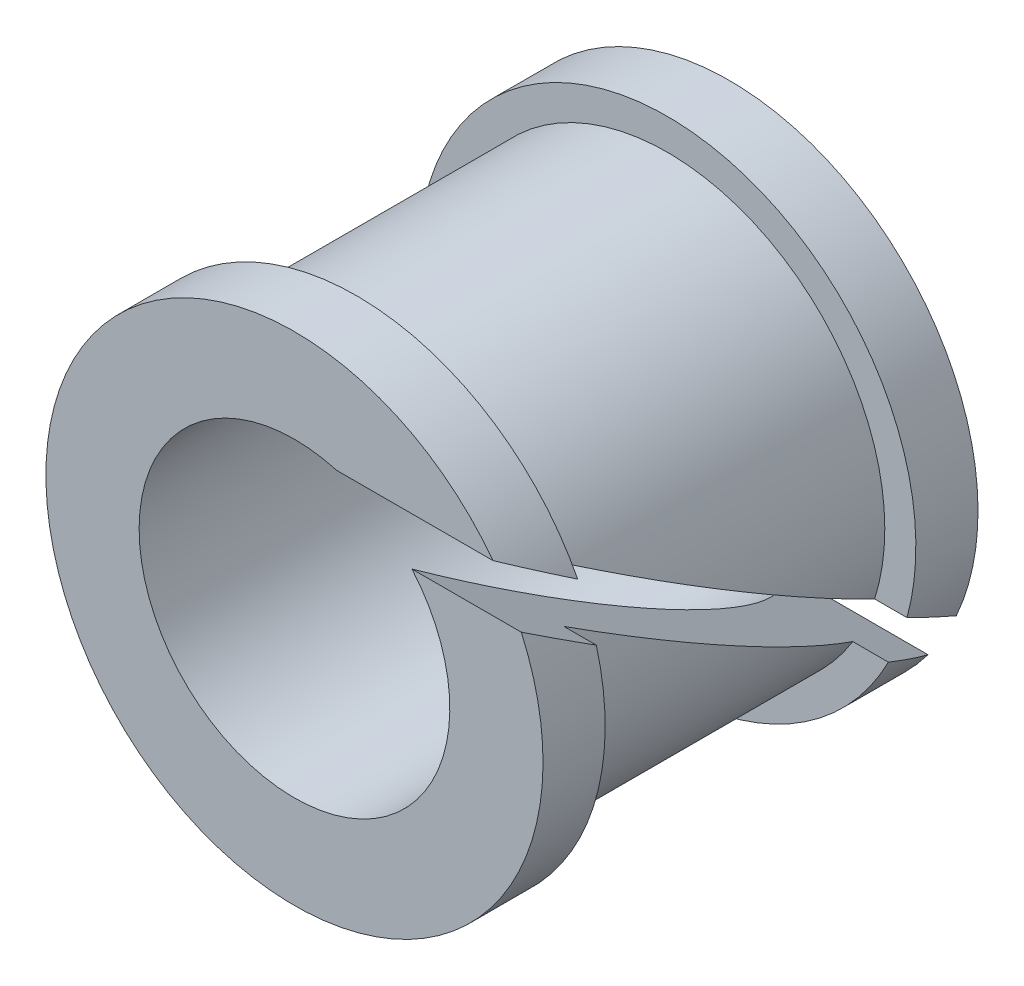
SolidWorks part; units mm, degrees
ref_plane "Front Plane" through (0, 0, 0) normal (0, 0, 1) x (1, 0, 0)
ref_plane "Top Plane" through (0, 0, 0) normal (0, 1, 0) x (1, 0, 0)
ref_plane "Right Plane" through (0, 0, 0) normal (1, 0, 0) x (0, 0, -1)
sketch "Sketch1" plane through (0, 0, 0) normal (1, 0, 0) x (0, 0, -1)
  line L0 (-1.5, 2.4) -> (-1.5, 2.1)
  line L1 (-1.5, 2.1) -> (1.5, 2.1)
  line L2 (1.5, 2.1) -> (1.5, 2.4)
  line L3 (1.5, 2.4) -> (2.1, 2.4)
  line L4 (2.1, 2.4) -> (2.1, 0)
  line L5 (0, 0) -> (0, 2.1) construction
  line L10 (-2.1, 0) -> (-2.1, 2.4)
  line L11 (-2.1, 2.4) -> (-1.5, 2.4)
  line L12 (-2.1, 0) -> (2.1, 0)
  dimension "D1" = 4.2
  dimension "D2" = 2.4
  dimension "D3" = 0.6
  dimension "D4" = 2.1
revolve "Revolve1" add sketch "Sketch1" angle 360 about L12
hole_wizard "Ø3.0mm Dowel Hole1" positions "Sketch2" profile "Sketch3" hole size "Ø3.0" standard "ANSI Metric" end condition through all
sketch "Sketch2" plane through (0, 0, 2.1) normal (0, 0, 1) x (1, 0, 0)
  point P0 (0, 0)
sketch "Sketch3" plane through (0, 0, 2.1) normal (1, 0, 0) x (0, -1, 0)
  line L0 (0, 0) -> (0, 4.2)
  line L1 (0, 4.2) -> (1.5, 4.2)
  line L2 (1.5, 4.2) -> (1.5, 0)
  line L5 (1.5, 0) -> (0, 0)
  line L11 (0, -6.35) -> (0, 107.95) construction
  dimension "Thru Hole Dia." = 3
  dimension "Thru Hole Depth" = 4.2
sketch "Sketch4" plane through (0, 0, 0) normal (1, 0, 0) x (0, 0, -1)
  line L0 (-2.1, 1.2124) -> (2.1, -1.2124) construction
  line L1 (-2.1, 2.4) -> (-2.1, -2.4) construction
  line L2 (2.1, -2.4) -> (2.1, 2.4) construction
  line L3 (-2.1, 0) -> (2.1, 0) construction
  line L4 (2.1, -1.5) -> (2.1, 1.5) construction
  line L5 (-2.3, 1.097) -> (-2.1, 1.4434)
  line L6 (-2.3, 1.097) -> (2.1, -1.4434)
  line L7 (-2.1, 1.4434) -> (2.3, -1.097)
  line L8 (2.1, -1.4434) -> (2.3, -1.097)
  line L9 (-2.1, 1.2124) -> (-2.2, 1.2702) construction
  point P11 (0, 0)
  dimension "D1" = 30
  dimension "D2" = 0.4
extrude "Cut-Extrude1" cut sketch "Sketch4" along normal through all
